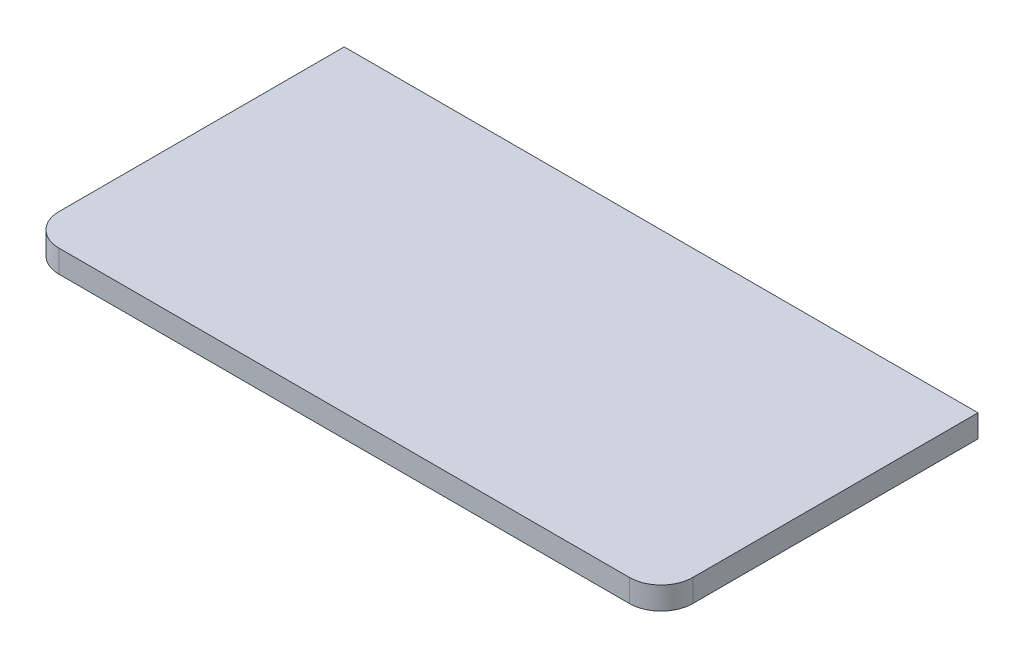
SolidWorks part; units mm, degrees
material "Plain Carbon Steel"
ref_plane "Front Plane" through (0, 0, 0) normal (0, 0, 1) x (1, 0, 0)
ref_plane "Top Plane" through (0, 0, 0) normal (0, 1, 0) x (1, 0, 0)
ref_plane "Right Plane" through (0, 0, 0) normal (1, 0, 0) x (0, 0, -1)
sketch "Sketch1" plane through (0, 0, 0) normal (0, 1, 0) x (1, 0, 0)
  line L1 (-140, -70) -> (140, -70)
  line L2 (-140, -70) -> (-140, 70)
  line L3 (-140, 70) -> (140, 70)
  line L4 (140, -70) -> (140, 70)
  line L5 (-140, -70) -> (140, 70) construction
  line L6 (-140, 70) -> (140, -70) construction
  point P0 (0, 0)
  dimension "D1" = 280
  dimension "D2" = 140
extrude "Boss-Extrude1" add sketch "Sketch1" along normal blind 10
fillet "Fillet1" radius 14 2 edges at (140, 5, 70) (-140, 5, 70)
